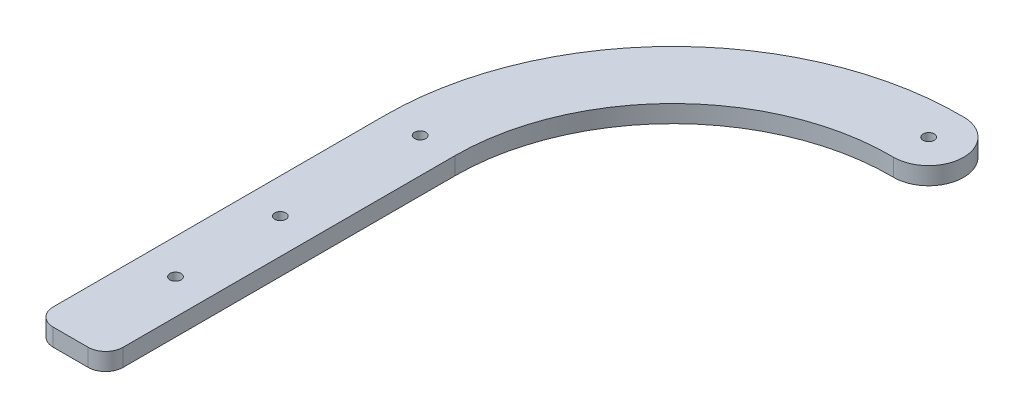
SolidWorks part; units mm, degrees
ref_plane "前基準面" through (0, 0, 0) normal (0, 0, 1) x (1, 0, 0)
ref_plane "上基準面" through (0, 0, 0) normal (0, 1, 0) x (1, 0, 0)
ref_plane "右基準面" through (0, 0, 0) normal (1, 0, 0) x (0, 0, -1)
sketch "草圖1" plane through (0, 0, 0) normal (0, 1, 0) x (1, 0, 0)
  line L0 (0, 50) -> (0, 100)
  line L1 (0, 50) -> (0, 0)
  line L2 (0, 0) -> (20, 0)
  line L3 (20, 0) -> (20, 50)
  line L4 (20, 100) -> (20, 50)
  line L5 (0, 100) -> (20, 100) construction
  line L7 (0, 50) -> (20, 50) construction
  arc A0 (0, 100) -> (83.2934, 182.3318) centre (82.3373, 100) cw
  arc A1 (83.2934, 182.3318) -> (83.0612, 162.3331) centre (83.1773, 172.3325) cw
  arc A2 (83.0612, 162.3331) -> (20, 100) centre (82.3373, 100) ccw
  dimension "D1" = 50
  dimension "D2" = 50
  dimension "D3" = 20
extrude "伸長1" add sketch "草圖1" along normal blind 5
sketch "草圖2" plane through (0, 5, 0) normal (0, 1, 0) x (1, 0, 0)
  line L0 (10, 0) -> (10, 60) construction
  line L1 (0, 0) -> (20, 0) construction
  line L2 (83.1773, 162.3325) -> (83.1773, 172.3325) construction
  line L3 (20, 100) -> (0, 100) construction
  circle A0 centre (10, 60) radius 1.6
  circle A1 centre (10, 30) radius 1.6
  arc A2 (83.0612, 162.3331) -> (83.2934, 182.3318) centre (83.1773, 172.3325) ccw construction
  arc A3 (83.1773, 172.3325) -> (10, 100) centre (83.1773, 99.1503) ccw construction
  circle A4 centre (83.1773, 172.3325) radius 1.6
  circle A5 centre (10, 100) radius 1.6
  dimension "D2" = 3.2
  dimension "D3" = 3.2
  dimension "D4" = 3.2
  dimension "D5" = 3.2
  dimension "D1" = 30
extrude "伸長2" cut sketch "草圖2" against normal through all
fillet "圓角1" radius 5 2 edges at (20, 2.5, 0) (0, 2.5, 0)
